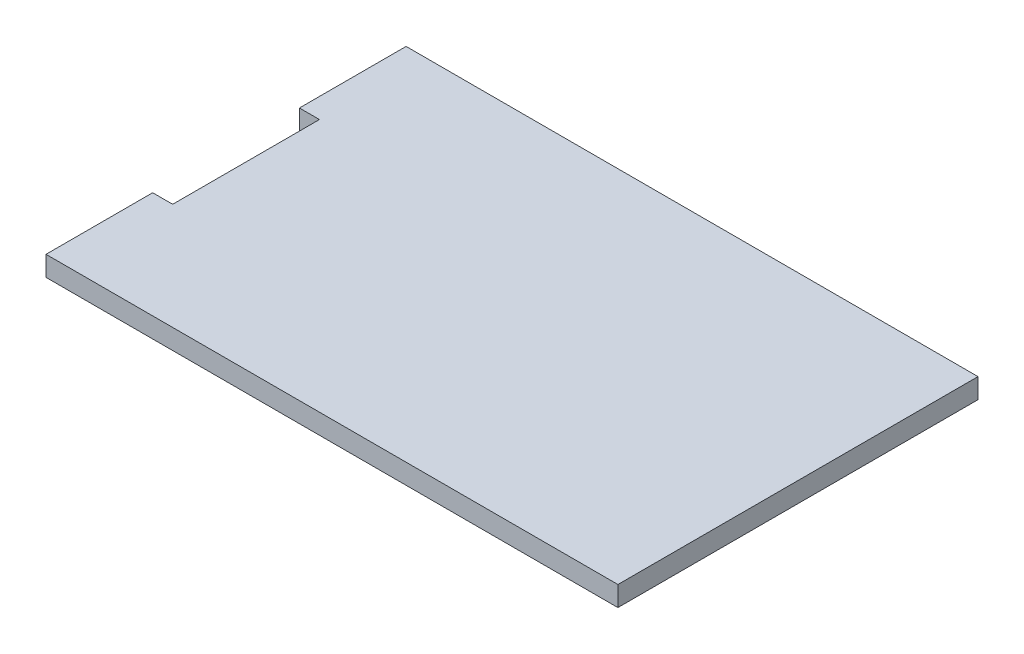
SolidWorks part; units mm, degrees
material "PMMA"
ref_plane "Front Plane" through (0, 0, 0) normal (0, 0, 1) x (1, 0, 0)
ref_plane "Top Plane" through (0, 0, 0) normal (0, 1, 0) x (1, 0, 0)
ref_plane "Right Plane" through (0, 0, 0) normal (1, 0, 0) x (0, 0, -1)
sketch "Sketch1" plane through (0, 0, 0) normal (0, 1, 0) x (1, 0, 0)
  line L0 (-42.8625, 0) -> (42.8625, 0) construction
  line L1 (-42.8625, -26.9875) -> (42.8625, -26.9875)
  line L2 (-42.8625, -26.9875) -> (-42.8625, -11)
  line L3 (-42.8625, 26.9875) -> (42.8625, 26.9875)
  line L4 (42.8625, -26.9875) -> (42.8625, 26.9875)
  line L5 (-42.8625, -26.9875) -> (42.8625, 26.9875) construction
  line L6 (-42.8625, 26.9875) -> (42.8625, -26.9875) construction
  line L7 (-42.8625, 11) -> (-39.8625, 11)
  line L8 (-39.8625, 11) -> (-39.8625, -11)
  line L9 (-39.8625, -11) -> (-42.8625, -11)
  line L10 (-42.8625, 11) -> (-42.8625, 26.9875)
  point P0 (0, 0)
  point P10 (-41.3625, -11)
  dimension "D1" = 85.725
  dimension "D2" = 53.975
  dimension "D3" = 11
  dimension "D4" = 11
  dimension "D5" = 3
extrude "Boss-Extrude1" add sketch "Sketch1" along normal blind 3
